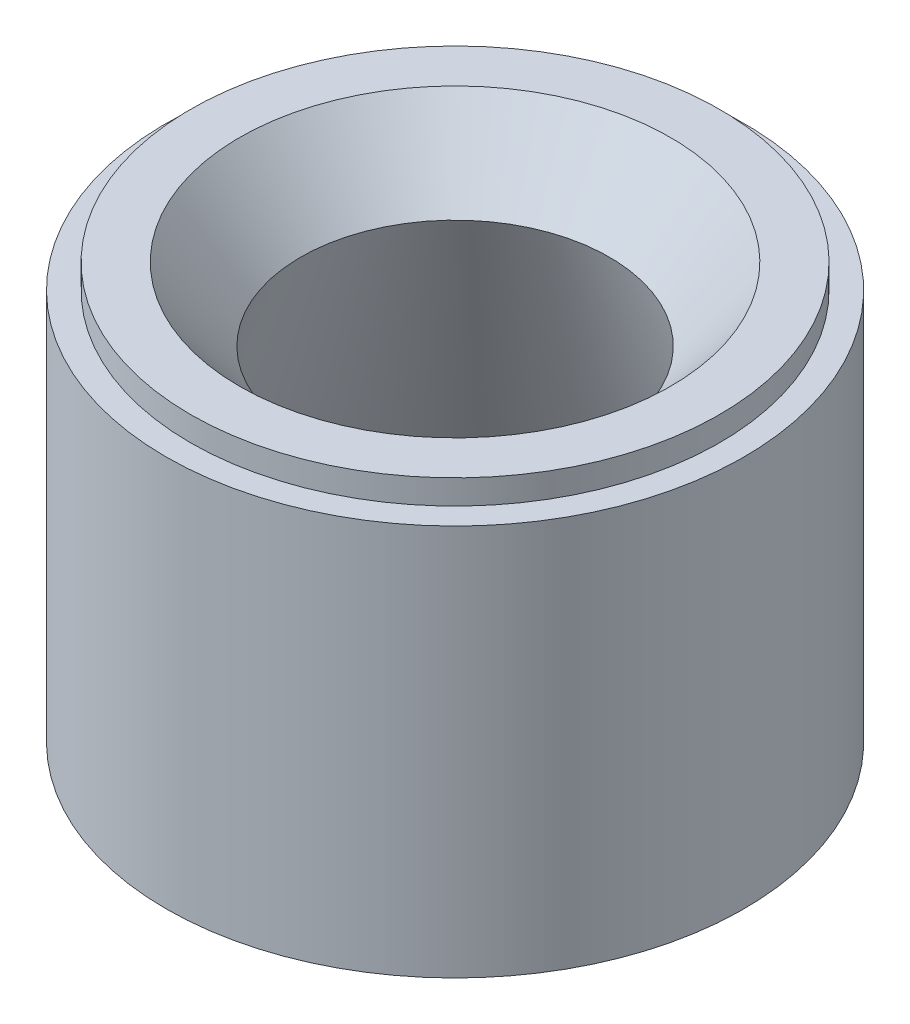
SolidWorks part; units mm, degrees
ref_plane "Front Plane" through (0, 0, 0) normal (0, 0, 1) x (1, 0, 0)
ref_plane "Top Plane" through (0, 0, 0) normal (0, 1, 0) x (1, 0, 0)
ref_plane "Right Plane" through (0, 0, 0) normal (1, 0, 0) x (0, 0, -1)
sketch "Sketch2" plane through (0, 0, 0) normal (0, 0, 1) x (1, 0, 0)
  line L0 (-55.95, 0) -> (-68.65, 0)
  line L1 (-68.65, 0) -> (-68.65, -6.35)
  line L2 (-68.65, -6.35) -> (-75, -6.35)
  line L3 (-75, -6.35) -> (-75, -107.95)
  line L4 (-75, -107.95) -> (-72.46, -107.95)
  line L5 (-72.46, -107.95) -> (-40.0613, -18.9354)
  line L6 (-40.0613, -18.9354) -> (-55.95, 0)
  line L7 (0, 0) -> (0, -209.55) construction
  dimension "D1" = 75
  dimension "D2" = 6.35
  dimension "D3" = 6.35
  dimension "D4" = 101.6
  dimension "D5" = 12.7
  dimension "D6" = 2.54
  dimension "D7" = 20
  dimension "D8" = 130
revolve "Revolve1" add sketch "Sketch2" angle 360 about L7
equation "\"CF_OD_A\"= 4.015in"
equation "\"CF_ID_A\"= 3.904in"
equation "\"KF_ID_A\"= 4.015in ' Kevlar airframe ID"
equation "\"CF_OD_C\"= 3.894in ' VERIFY Coupler OD"
equation "\"CF_ID_C\"= 3.783in ' VERIFY Coupler ID"
equation "\"KF_WALL\"= 0.0625in"
equation "\"AF_01\"=10in"
equation "\"AF_02\"=16in"
equation "\"AF_03\"=in"
equation "\"B_CF_OD\"=6.17in"
equation "\"B_CF_ID\"=6in"
equation "\"B_CF_WT\"=0.085in"
equation "\"B_Fin_Root\"=18in"
